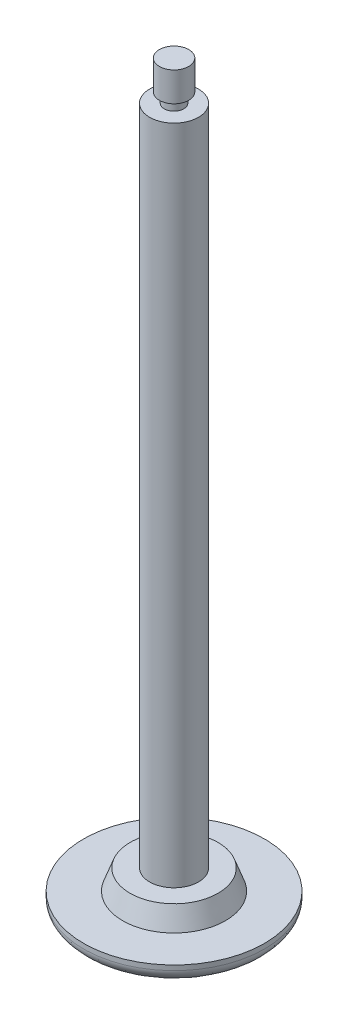
SolidWorks part; units mm, degrees
material "Plain Carbon Steel"
ref_plane "Front Plane" through (0, 0, 0) normal (0, 0, 1) x (1, 0, 0)
ref_plane "Top Plane" through (0, 0, 0) normal (0, 1, 0) x (1, 0, 0)
ref_plane "Right Plane" through (0, 0, 0) normal (1, 0, 0) x (0, 0, -1)
sketch "Sketch1" plane through (0, 0, 0) normal (0, 0, 1) x (1, 0, 0)
  line L0 (0, 0) -> (0, 155.5) construction
  line L1 (0, 0) -> (0, 1) construction
  line L2 (18.5, 7) -> (18.5, 8)
  line L3 (18.5, 8) -> (10.5, 8)
  line L7 (3, 155.5) -> (0, 155.5)
  line L8 (0, 155.5) -> (0, 1)
  line L12 (9, 12.1212) -> (10.5, 8)
  line L13 (2, 147.5) -> (2, 149.5)
  line L14 (2, 149.5) -> (3, 149.5)
  line L15 (3, 149.5) -> (3, 155.5)
  line L17 (0, -5.5) -> (0, -7.5334) construction
  line L18 (2, 147.5) -> (5, 147.5)
  line L19 (5, 147.5) -> (5, 12.1212)
  line L20 (5, 12.1212) -> (9, 12.1212)
  ellipse E0 centre (0, 7) end of major axis (18.5, 7) minor radius 6 (0, 1) -> (18.5, 7) ccw
  dimension "D2" = 10
  dimension "D3" = 7
  dimension "D4" = 21
  dimension "D5" = 6
  dimension "D6" = 18
  dimension "D7" = 110
  dimension "D8" = 146.5
  dimension "D9" = 2
  dimension "D10" = 6
  dimension "D11" = 37
  dimension "D12" = 6
  dimension "D13" = 4
  dimension "D14" = 1
revolve "Revolve1" add sketch "Sketch1" angle 360 about L0
ref_point "Apex"
